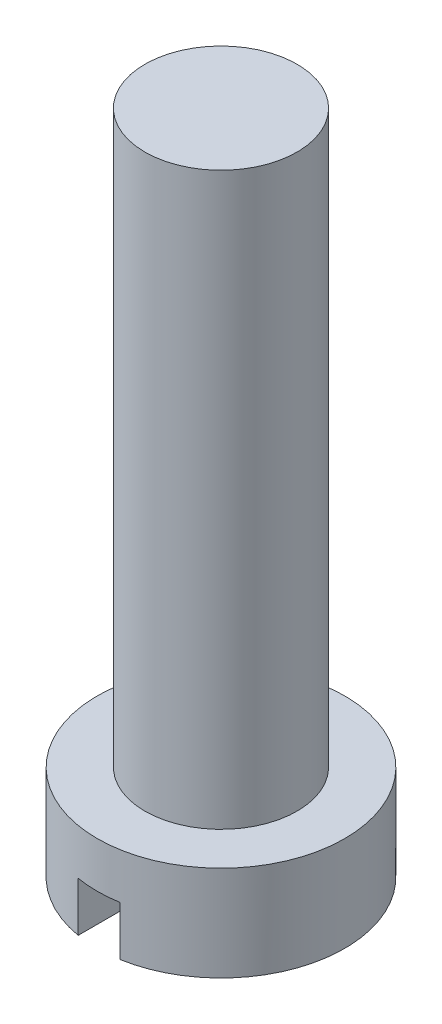
SolidWorks part; units mm, degrees
material "AISI 1020"
ref_plane "Спереди" through (0, 0, 0) normal (0, 0, 1) x (1, 0, 0)
ref_plane "Сверху" through (0, 0, 0) normal (0, 1, 0) x (1, 0, 0)
ref_plane "Справа" through (0, 0, 0) normal (1, 0, 0) x (0, 0, -1)
sketch "Эскиз1" plane through (0, 0, 0) normal (0, 1, 0) x (1, 0, 0)
  circle A0 centre (0, 0) radius 6.5
  dimension "D1" = 13
extrude "Бобышка-Вытянуть1" add sketch "Эскиз1" along normal blind 5
sketch "Эскиз2" plane through (0, 0, 0) normal (0, 0, 1) x (1, 0, 0)
  line L0 (-6.5, 0) -> (6.5, 0) construction
  line L1 (-1.1, 2.6) -> (1.1, 2.6)
  line L2 (-1.1, 2.6) -> (-1.1, 0)
  line L3 (-1.1, 0) -> (1.1, 0)
  line L4 (1.1, 2.6) -> (1.1, 0)
  dimension "D1" = 2.2
  dimension "D2" = 2.6
extrude "Вырез-Вытянуть1" cut sketch "Эскиз2" against normal mid plane 13.9
sketch "Эскиз3" plane through (0, 5, 0) normal (0, 1, 0) x (1, 0, 0)
  line L0 (-1000, 0) -> (49000, 0) construction
  line L1 (0, -1000) -> (0, 49000) construction
  circle A0 centre (0, 0) radius 4
  dimension "D1" = 8
extrude "Бобышка-Вытянуть2" add sketch "Эскиз3" along normal blind 30
cosmetic thread "Условное изображение резьбы1" parameters "D2"=6.891
